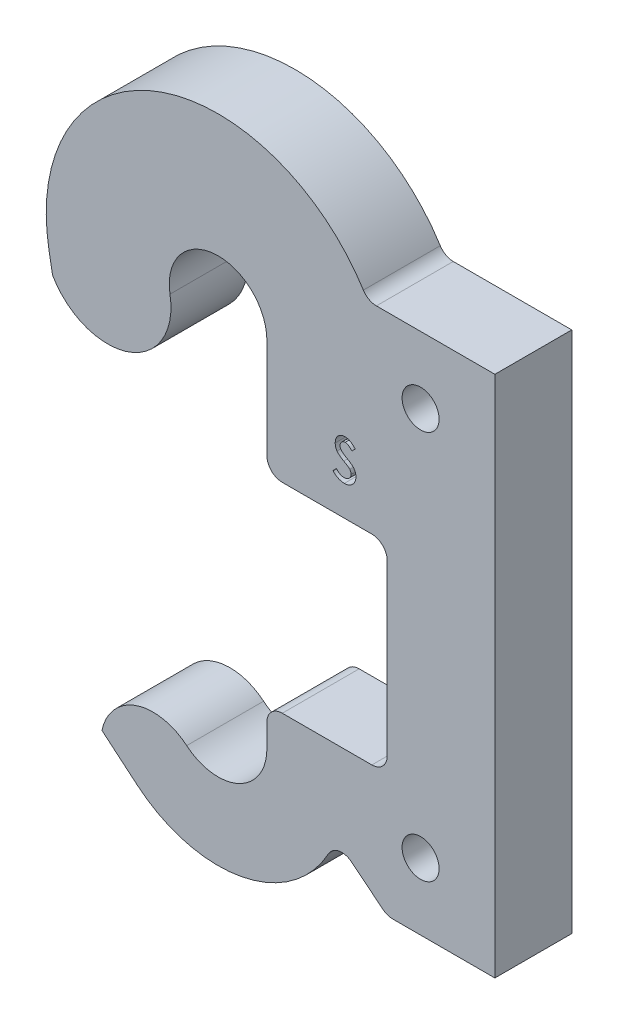
SolidWorks part; units mm, degrees
ref_plane "Front Plane" through (0, 0, 0) normal (0, 0, 1) x (1, 0, 0)
ref_plane "Top Plane" through (0, 0, 0) normal (0, 1, 0) x (1, 0, 0)
ref_plane "Right Plane" through (0, 0, 0) normal (1, 0, 0) x (0, 0, -1)
sketch "Main Geometry" plane through (0, 0, 0) normal (0, 0, 1) x (1, 0, 0)
  line L0 (0, -26.7735) -> (0, 29.7025) construction
  line L1 (-29.8398, 0) -> (33.7757, 0) construction
  line L2 (11, -21.6476) -> (11, 17) construction
  line L3 (11, 17) -> (11, -25.7424) construction
  dimension "vertical offset" = 17
  dimension "horizontal offset" = 11
  dimension "device angle" = 360
sketch "Cart Clip Geometry" plane through (0, 0, 0) normal (0, 0, 1) x (1, 0, 0)
  line L0 (10, 9.2735) -> (11, -10.0482) construction
  line L1 (11.175, 10.5) -> (8.175, -10.5)
  line L2 (7.0852, 11.5) -> (-7.0852, 11.5) construction
  line L3 (-29.8398, 0) -> (33.7757, 0) construction
  line L4 (11, -21.6476) -> (11, 17) construction
  line L6 (-7.0852, 0) -> (7.0852, 0) construction
  line L7 (7.0852, -11.5) -> (-7.0852, -11.5) construction
  line L8 (0, 11.5) -> (-7.5717, 10.1649) construction
  line L9 (0, -11.5) -> (-5.2448, -17.7505) construction
  line L10 (3.175, 11.5) -> (3.175, -11.5)
  line L11 (-11.0052, 9.5595) -> (-10.7668, 8.2074)
  line L12 (-5.2548, -17.7624) -> (-7.5529, -15.8341)
  line L13 (11.175, 10.5) -> (11.175, 11.5)
  line L14 (8.175, -11.5) -> (8.175, -10.5)
  arc A0 (-3.1268, 10.9487) -> (3.175, 11.5) centre (0, 11.5) cw
  arc A1 (-2.0409, -13.9322) -> (3.175, -11.5) centre (0, -11.5) ccw
  arc A2 (-11.0052, 9.5595) -> (11.175, 11.5) centre (0, 11.5) cw
  arc A3 (-5.2548, -17.7624) -> (8.175, -11.5) centre (0, -11.5) ccw
  arc A4 (-3.1268, 10.9487) -> (-10.7668, 8.2074) centre (-7.182, 10.2336) cw
  arc A5 (-2.0409, -13.9322) -> (-7.5529, -15.8341) centre (-4.2263, -16.5367) ccw
  point P5 (0, 11.5)
  point P10 (0, 0)
  point P36 (10.5, -0.3874)
  dimension "D1" = 1
  dimension "rail radius" = 3.175
  dimension "bottom rail radius" = 3.175
  dimension "rail separation" = 11.5
  dimension "top clip grab angle" = 10
  dimension "bottom clip grab angle" = 50
  dimension "top clip thickness" = 8
  dimension "bottom clip thickness" = 5
  dimension "top clip end extension" = 1.3729
  dimension "bottom clip end extension" = 3
  dimension "top clip vertical extension" = 1
extrude "Cart Clip" add sketch "Cart Clip Geometry" against normal blind 5
sketch "hole block geometry" plane through (0, 0, 0) normal (0, 0, 1) x (1, 0, 0)
  line L0 (11, 17) -> (11, -17)
  line L2 (11, 17) -> (11, -25.7424) construction
  line L3 (11, -17) -> (18, -17)
  line L4 (18, -17) -> (18, 17)
  line L5 (18, 17) -> (11, 17)
  line L6 (18, 0) -> (11, 0) construction
  dimension "D1" = 34
  dimension "D2" = 7
extrude "hole block" add sketch "hole block geometry" against normal blind 5 separate body
sketch "hole geometry" plane through (0, 0, 0) normal (0, 0, 1) x (1, 0, 0)
  line L0 (18, -17) -> (18, 17) construction
  line L1 (18, 0) -> (11, 0) construction
  circle A0 centre (13.17, 12.655) radius 1.205
  dimension "D1" = 4.83
  dimension "D2" = 12.655
extrude "holes" cut sketch "hole geometry" against normal through all
pattern_linear "LPattern1" count 2 spacing 25.31 along (0, -1, 0) of "holes"
sketch "nut slot geometry" plane through (0, 0, 0) normal (0, 0, 1) x (1, 0, 0)
  line L0 (11, -9) -> (11, 4)
  line L1 (11, 4) -> (-5, 4)
  line L2 (-5, 4) -> (-5, -9)
  line L3 (-5, -9) -> (11, -9)
  line L4 (18, 0) -> (11, 0) construction
  dimension "D1" = 13
  dimension "D2" = 16
  dimension "D3" = 7
  dimension "D4" = 4
sketch "joint geometry" plane through (0, 0, 0) normal (0, 0, 1) x (1, 0, 0)
  line L0 (9.7278, 17) -> (11, 17)
  line L1 (11, 17) -> (11, -17)
  line L2 (11, -17) -> (7.6744, -14.3166)
  line L3 (7.6744, -14.3166) -> (9.7278, 17)
  arc A0 (-5.2548, -17.7624) -> (8.175, -11.5) centre (0, -11.5) ccw construction
  arc A1 (11.175, 11.5) -> (-11.0052, 9.5595) centre (0, 11.5) ccw construction
  point P4 (8.175, -10.5)
  point P9 (7.411, -14.9508)
  point P13 (9.7278, 17)
  point P17 (7.6744, -14.3166)
extrude "joint" add sketch "joint geometry" against normal blind 5
extrude "nut slot" cut sketch "nut slot geometry" against normal through all
fillet "Fillet1" radius 1 7 edges at (11, -17, -2.5) (3.175, -9, -2.5) (3.175, 4, -2.5) (11, 4, -2.5) (11, -9, -2.5) (7.6744, -14.3166, -2.5) (9.7278, 17, -2.5)
sketch "swing marker" plane through (0, 0, 0) normal (0, 0, 1) x (1, 0, 0)
  text T0 "s"
extrude "Cut-Extrude1" cut sketch "swing marker" against normal blind 10
